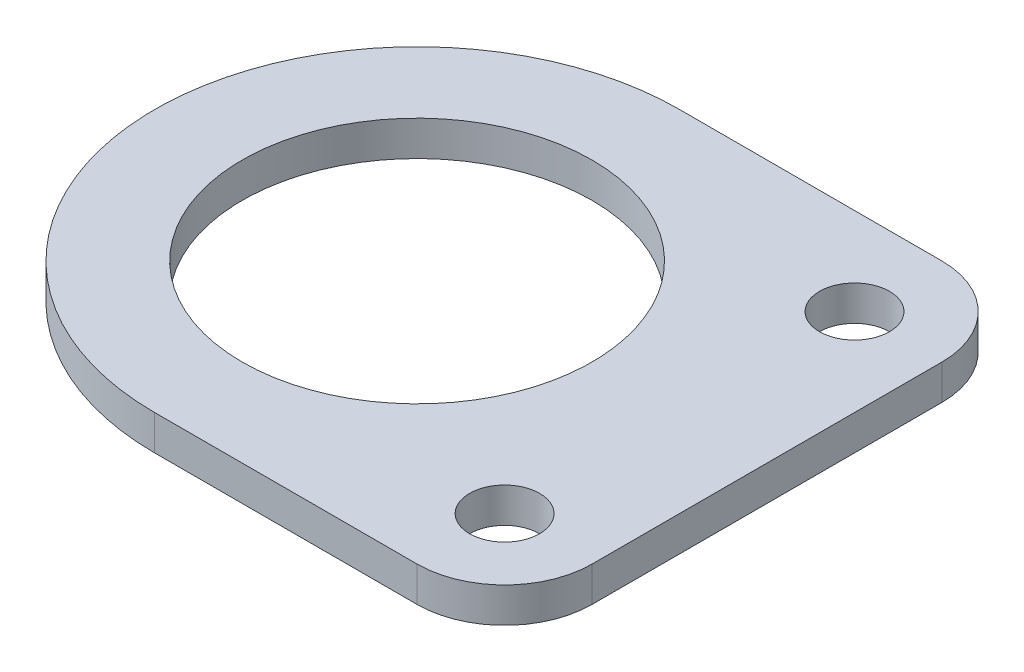
SolidWorks part; units mm, degrees
material "1060 Alloy"
ref_plane "Front Plane" through (0, 0, 0) normal (0, 0, 1) x (1, 0, 0)
ref_plane "Top Plane" through (0, 0, 0) normal (0, 1, 0) x (1, 0, 0)
ref_plane "Right Plane" through (0, 0, 0) normal (1, 0, 0) x (0, 0, -1)
sketch "Sketch2" plane through (0, 0, 0) normal (0, 0, 1) x (1, 0, 0)
  line L0 (-10, 3) -> (-10, 2)
  line L1 (55, 0) -> (-55, 0) construction
  line L2 (-10, 0) -> (-15, 0)
  line L3 (-15, 0) -> (-15, 2)
  line L4 (-15, 2) -> (-11, 2)
  line L5 (-11, 2) -> (-11, 3)
  line L6 (-11, 3) -> (-10, 3)
  line L7 (0, -44.7868) -> (0, 44.7868) construction
  line L11 (-10, 2) -> (-10, 0)
  dimension "D1" = 1
  dimension "D2" = 2
  dimension "D3" = 4
  dimension "D4" = 1
  dimension "D5" = 10
ref_axis "Axis1" through (0, 45.8673, 0) along (0, -1, 0)
revolve "Revolve1" add sketch "Sketch2" angle 360 about axis through (0, 45.8673, 0) along (0, -1, 0)
sketch "Sketch3" plane through (0, 0, 0) normal (0, -1, 0) x (1, 0, 0)
  line L0 (0, -44.7868) -> (0, 44.7868) construction
  line L1 (0, -15) -> (15, -15)
  line L2 (20, -10) -> (20, 10)
  line L3 (15, 15) -> (0, 15)
  arc A1 (0, 15) -> (0, -15) centre (0, 0) cw
  circle A2 centre (0, 0) radius 15 construction
  arc A3 (15, -15) -> (20, -10) centre (15, -10) ccw
  arc A4 (20, 10) -> (15, 15) centre (15, 10) ccw
  dimension "D2" = 5
  dimension "D1" = 20
extrude "Boss-Extrude1" add sketch "Sketch3" against normal blind 2
sketch "Sketch4" plane through (0, 0, 0) normal (0, -1, 0) x (1, 0, 0)
  circle A0 centre (15, 10) radius 2
  circle A1 centre (15, -10) radius 2
  dimension "D1" = 4
  dimension "D2" = 4
  dimension "D3" = 0
  dimension "D4" = 0
  dimension "D5" = 20
extrude "Cut-Extrude1" cut sketch "Sketch4" against normal blind 2
sketch "Sketch6" plane through (0, 3, 0) normal (0, 1, 0) x (1, 0, 0)
  circle A0 centre (0, 0) radius 11
extrude "Cut-Extrude2" cut sketch "Sketch6" against normal blind 1
